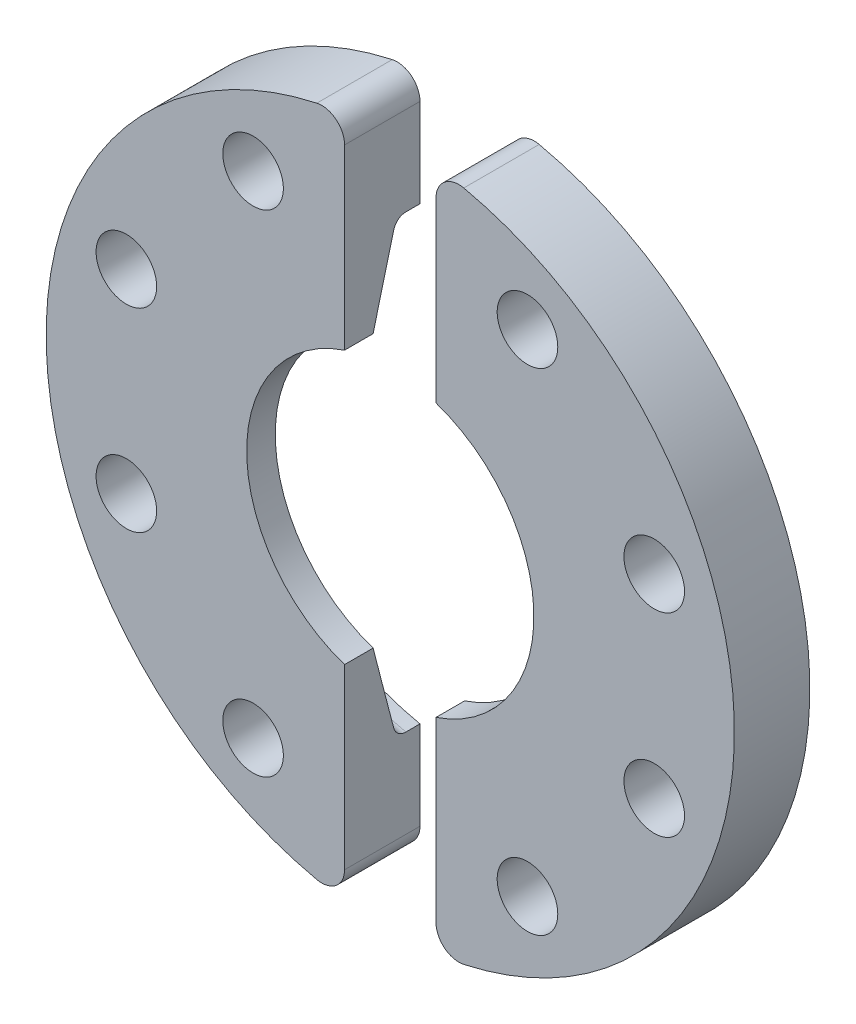
SolidWorks part; units mm, degrees
ref_plane "Front Plane" through (0, 0, 0) normal (0, 0, 1) x (1, 0, 0)
ref_plane "Top Plane" through (0, 0, 0) normal (0, 1, 0) x (1, 0, 0)
ref_plane "Right Plane" through (0, 0, 0) normal (1, 0, 0) x (0, 0, -1)
ref_plane "Plane1" through (0, 18.1202, 0) normal (0, 1, 0) x (1, 0, 0)
sketch "Sketch2" plane through (0, 18.1202, 0) normal (0, 1, 0) x (1, 0, 0)
  line L0 (-2.3744, -37.5916) -> (22.6956, -37.5916) construction
  line L1 (-2.3744, -37.5916) -> (22.6956, -37.5916) construction
  line L2 (-9.0982, -35.79) -> (29.4194, -35.79)
  line L3 (30.1606, -34.8241) -> (-9.8394, -34.8241)
  line L4 (-9.8394, -34.8241) -> (30.1606, -34.8241)
  line L5 (30.1606, -34.8241) -> (30.1606, -32.5916)
  line L6 (30.1606, -32.5916) -> (-9.8394, -32.5916)
  line L7 (-9.8394, -32.5916) -> (-9.8394, -34.8241)
  line L9 (30.1606, -34.8241) -> (30.1606, -32.5916) construction
  line L12 (-2.3744, -37.5916) -> (22.6956, -37.5916)
  line L13 (22.6956, -37.5916) -> (29.4194, -35.79)
  line L14 (29.4194, -35.79) -> (-9.0982, -35.79)
  line L15 (-9.0982, -35.79) -> (-2.3744, -37.5916)
  line L17 (22.6956, -37.5916) -> (29.4194, -35.79) construction
  line L20 (10.1606, -37.5916) -> (10.1606, -43.432) construction
  line L21 (22.7215, -37.6882) -> (29.4453, -35.8866)
  line L22 (30.2606, -34.8241) -> (30.2606, -32.5916)
  line L23 (30.2606, -32.5916) -> (40.2606, -32.5916) construction
  line L24 (40.2606, -32.5916) -> (40.2606, -40.1882)
  line L25 (22.7215, -37.6882) -> (22.7215, -40.1882)
  line L26 (22.7215, -40.1882) -> (40.2606, -40.1882)
  line L27 (30.2606, -33.5916) -> (40.2606, -33.5916)
  arc A0 (29.4453, -35.8866) -> (30.2606, -34.8241) centre (29.1606, -34.8241) ccw
  arc A2 (29.4194, -35.79) -> (30.1606, -34.8241) centre (29.1606, -34.8241) ccw
  arc A3 (-9.8394, -34.8241) -> (-9.0982, -35.79) centre (-8.8394, -34.8241) ccw
  arc A4 (29.4194, -35.79) -> (30.1606, -34.8241) centre (29.1606, -34.8241) ccw construction
  point P18 (0, 0)
  dimension "D4" = 0.1
  dimension "D5" = 10
  dimension "D6" = 2.5
  dimension "D7" = 1
  dimension "D1" = 0
  dimension "D2" = 0
  dimension "D3" = 0
revolve "Revolve2" add sketch "Sketch2" angle 360 about L20
sketch "Sketch3" plane through (0, 0, 40.1882) normal (0, 0, 1) x (1, 0, 0)
  line L0 (10.1606, -11.9798) -> (10.1606, 48.2202) construction
  line L1 (14.1606, -11.9798) -> (14.1606, 48.2202)
  line L2 (6.1606, -11.9798) -> (6.1606, 48.2202)
  line L3 (10.1606, 18.1202) -> (34.7606, 18.1202) construction
  line L4 (34.7606, 9.6202) -> (34.7606, 26.6202) construction
  line L5 (34.7606, 26.6202) -> (33.2455, 26.6202) construction
  line L6 (34.7606, 9.6202) -> (33.2455, 9.6202) construction
  line L7 (10.1606, -6.4798) -> (22.1606, -6.4798) construction
  circle A0 centre (10.1606, 18.1202) radius 24.6 construction
  circle A1 centre (10.1606, 18.1202) radius 30.1
  circle A2 centre (10.1606, 18.1202) radius 30.1 construction
  circle A3 centre (10.1606, 18.1202) radius 30.1 construction
  circle A4 centre (33.2455, 26.6202) radius 2.65
  circle A5 centre (33.2455, 9.6202) radius 2.65
  circle A6 centre (22.1606, -3.3544) radius 2.65
  circle A7 centre (22.1606, 39.5949) radius 2.65
  circle A8 centre (-12.9242, 26.6202) radius 2.65
  circle A9 centre (-12.9242, 9.6202) radius 2.65
  circle A10 centre (-1.8394, -3.3544) radius 2.65
  circle A11 centre (-1.8394, 39.5949) radius 2.65
  point P2 (0, 0)
  point P17 (34.7606, 18.1202)
  point P36 (0, 0)
  circle M4 centre (10.1606, 18.1202) radius 30.1
  circle M5 centre (10.1606, 18.1202) radius 12.5609
  dimension "D3" = 5.3
  dimension "D7" = 49.2
  dimension "D2" = 17
  dimension "D4" = 12
  dimension "D1" = 0
  dimension "D5" = 4
  dimension "D6" = 4
extrude "Cut-Extrude1" cut sketch "Sketch3" against normal blind 10 contours L2 L1 M4 M5 | L2 L1 M5 M4 | A11 | A8 | A9 | A10 | A6 | A5 | A4 | A7
fillet "Fillet1" radius 2 2 edges at (6.1606, -11.7128, 36.8899) (6.1606, 47.9533, 36.8899)
fillet "Fillet2" radius 2 2 edges at (14.1606, 47.9533, 36.8899) (14.1606, -11.7128, 36.8899)
